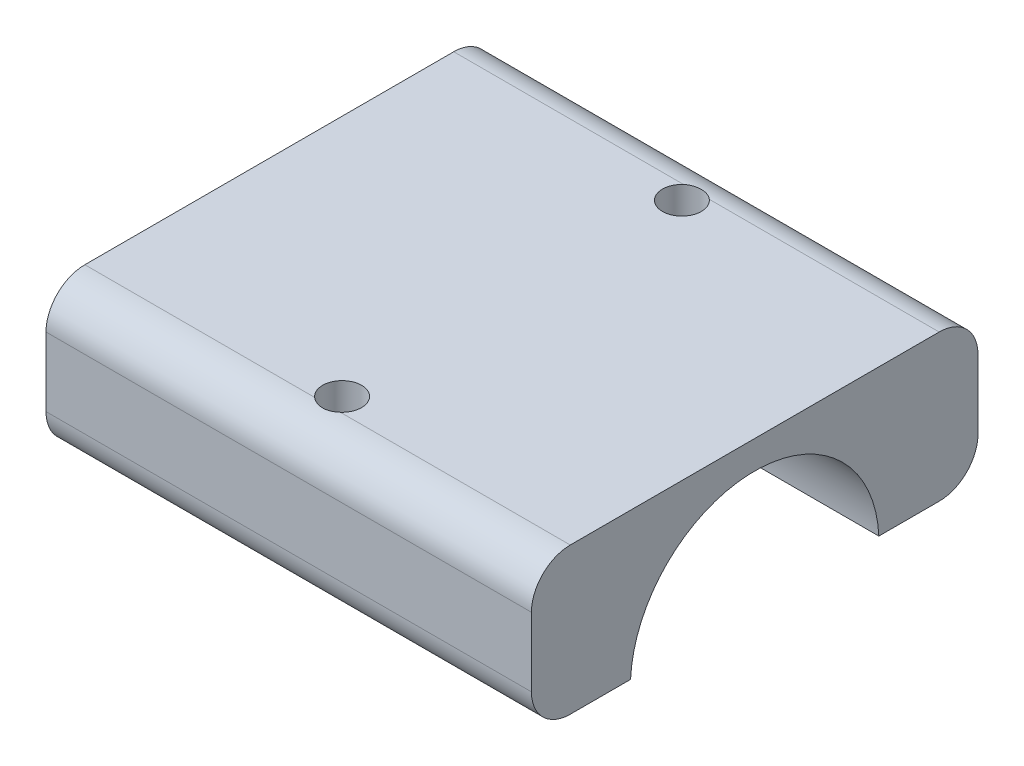
SolidWorks part; units mm, degrees
ref_plane "Front Plane" through (0, 0, 0) normal (0, 0, 1) x (1, 0, 0)
ref_plane "Top Plane" through (0, 0, 0) normal (0, 1, 0) x (1, 0, 0)
ref_plane "Right Plane" through (0, 0, 0) normal (1, 0, 0) x (0, 0, -1)
sketch "Sketch1" plane through (0, 0, 0) normal (1, 0, 0) x (0, 0, -1)
  line L0 (-19, 0.6) -> (19, 0.6)
  line L1 (23, 4.6) -> (23, 11.7)
  line L2 (19, 15.7) -> (-19, 15.7)
  line L3 (-23, 11.7) -> (-23, 4.6)
  arc A0 (19, 0.6) -> (23, 4.6) centre (19, 4.6) ccw
  arc A1 (23, 11.7) -> (19, 15.7) centre (19, 11.7) ccw
  arc A2 (-19, 15.7) -> (-23, 11.7) centre (-19, 11.7) ccw
  arc A3 (-23, 4.6) -> (-19, 0.6) centre (-19, 4.6) ccw
extrude "Boss-Extrude1" add sketch "Sketch1" along normal mid plane 50
sketch "Sketch2" plane through (0, 0, 0) normal (1, 0, 0) x (0, 0, -1)
  circle A0 centre (0, 0) radius 12.8
extrude "Cut-Extrude1" cut sketch "Sketch2" against normal through all and the other way through all
ref_plane "Plane1" through (0, 0.6, 0) normal (0, 1, 0) x (1, 0, 0)
sketch "Sketch3" plane through (0, 0.6, 0) normal (0, 1, 0) x (1, 0, 0)
  circle A0 centre (18, -17.5) radius 2
  circle A1 centre (18, 17.5) radius 2
  circle A2 centre (-18, -17.5) radius 2
  circle A3 centre (-18, 17.5) radius 2
extrude "Cut-Extrude2" cut sketch "Sketch3" along normal blind 7.5
ref_plane "Plane2" through (0, 15.7, 0) normal (0, 1, 0) x (1, 0, 0)
sketch "Sketch4" plane through (0, 15.7, 0) normal (0, 1, 0) x (1, 0, 0)
  circle A0 centre (0, -17.5) radius 2
  circle A1 centre (0, 17.5) radius 2
extrude "Cut-Extrude3" cut sketch "Sketch4" against normal blind 7.5
